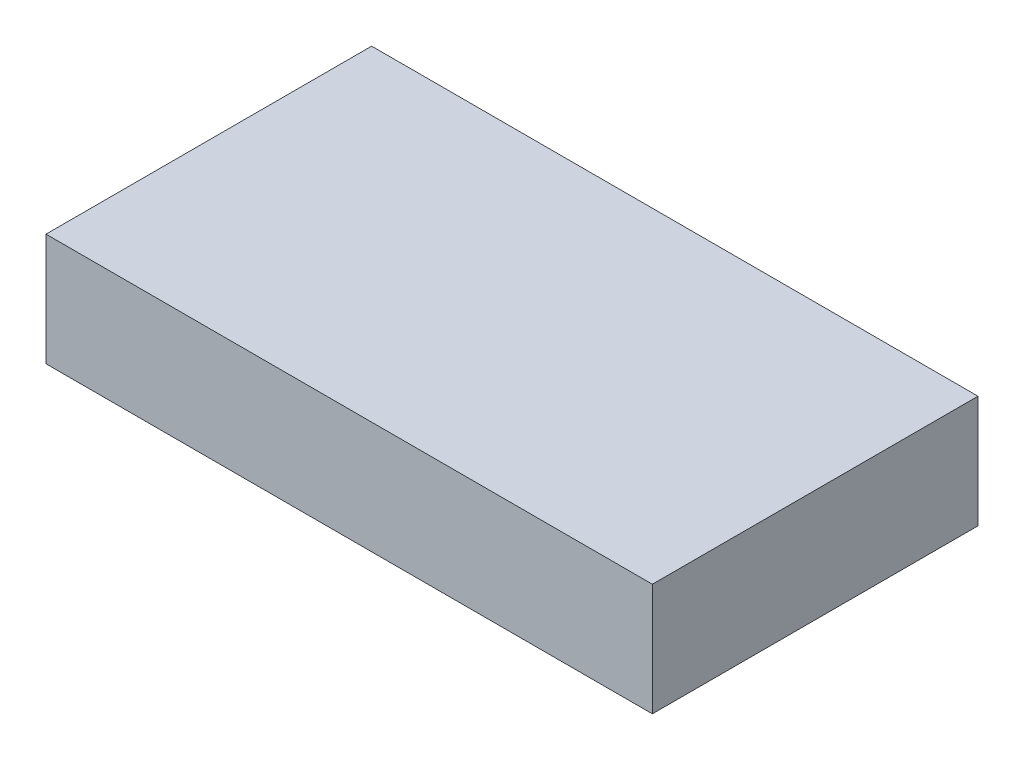
SolidWorks part; units mm, degrees
ref_plane "Front Plane" through (0, 0, 0) normal (0, 0, 1) x (1, 0, 0)
ref_plane "Top Plane" through (0, 0, 0) normal (0, 1, 0) x (1, 0, 0)
ref_plane "Right Plane" through (0, 0, 0) normal (1, 0, 0) x (0, 0, -1)
sketch "Sketch1" plane through (0, 0, 0) normal (0, 1, 0) x (1, 0, 0)
  line L1 (-25, -12.5) -> (25, -12.5) construction
  line L2 (-25, -12.5) -> (-25, 12.5) construction
  line L3 (-25, 12.5) -> (25, 12.5) construction
  line L4 (25, -12.5) -> (25, 12.5) construction
  line L5 (-25, -12.5) -> (25, 12.5) construction
  line L6 (-25, 12.5) -> (25, -12.5) construction
  line L7 (-27, 14.5) -> (27, 14.5)
  line L8 (-27, 14.5) -> (-27, -14.5)
  line L9 (-27, -14.5) -> (27, -14.5)
  line L10 (27, 14.5) -> (27, -14.5)
  line L11 (-27, 14.5) -> (27, -14.5) construction
  line L12 (-27, -14.5) -> (27, 14.5) construction
  point P0 (0, 0)
  point P6 (0, 0)
  dimension "D1" = 50
  dimension "D2" = 25
  dimension "D3" = 2
  dimension "D4" = 2
extrude "Boss-Extrude1" add sketch "Sketch1" along normal blind 10
